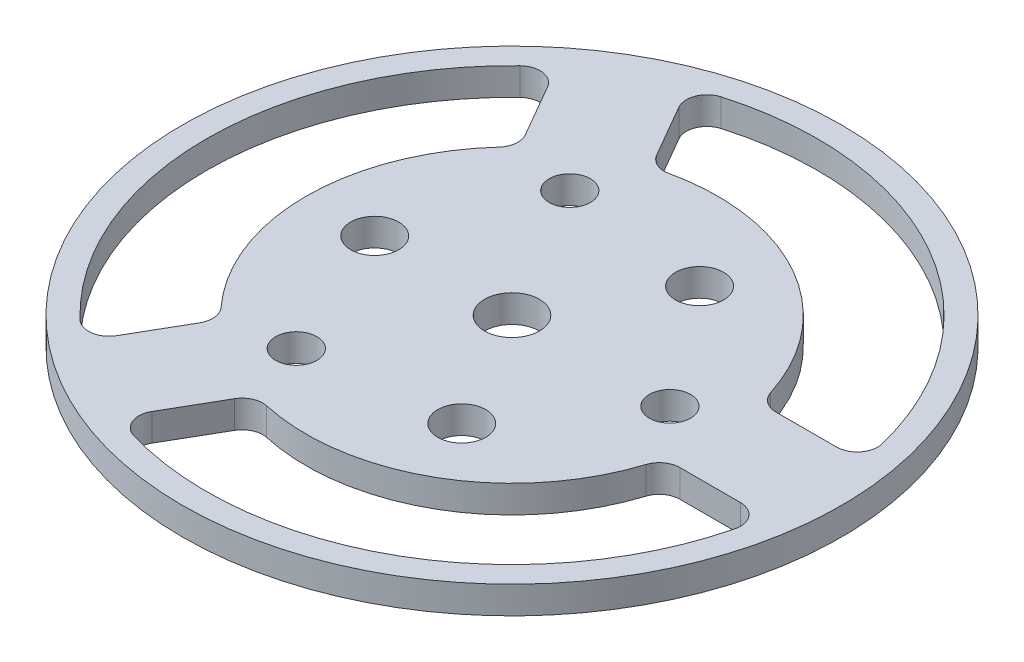
SolidWorks part; units mm, degrees
material "1060 Alloy"
ref_plane "Front Plane" through (0, 0, 0) normal (0, 0, 1) x (1, 0, 0)
ref_plane "Top Plane" through (0, 0, 0) normal (0, 1, 0) x (1, 0, 0)
ref_plane "Right Plane" through (0, 0, 0) normal (1, 0, 0) x (0, 0, -1)
sketch "Sketch1" plane through (0, 0, 0) normal (0, 1, 0) x (1, 0, 0)
  circle A0 centre (0, 0) radius 2
  circle A2 centre (0, 0) radius 24
  circle A3 centre (11.5, 0) radius 1.5
  circle A4 centre (-5.75, -9.9593) radius 1.5
  circle A5 centre (-5.75, 9.9593) radius 1.5
  point P13 (0, 0)
  dimension "D1" = 4
  dimension "D3" = 48
  dimension "D4" = 3
  dimension "D5" = 11.5
  dimension "D6" = 3
extrude "Boss-Extrude1" add sketch "Sketch1" along normal blind 2
sketch "Sketch2" plane through (0, 2, 0) normal (0, 1, 0) x (1, 0, 0)
  line L0 (21.973, 3.5) -> (14.586, 3.5)
  line L1 (21.973, -3.5) -> (14.586, -3.5)
  line L2 (-7.9554, -20.7792) -> (-4.2619, -14.3818)
  line L3 (-14.0176, -17.2792) -> (-10.3241, -10.8818)
  line L4 (-14.0176, 17.2792) -> (-10.3241, 10.8818)
  line L5 (-7.9554, 20.7792) -> (-4.2619, 14.3818)
  arc A0 (-14.0176, 17.2792) -> (-14.0176, -17.2792) centre (0, 0) ccw
  arc A1 (-10.3241, 10.8818) -> (-10.3241, -10.8818) centre (0, 0) ccw
  circle A2 centre (11.5, 0) radius 1.5 construction
  arc A3 (-4.2619, -14.3818) -> (14.586, -3.5) centre (0, 0) ccw
  arc A4 (-7.9554, -20.7792) -> (21.973, -3.5) centre (0, 0) ccw
  arc A5 (14.586, 3.5) -> (-4.2619, 14.3818) centre (0, 0) ccw
  arc A6 (21.973, 3.5) -> (-7.9554, 20.7792) centre (0, 0) ccw
  point P20 (0, 0)
  dimension "D1" = 44.5
  dimension "D2" = 30
  dimension "D3" = 3.5
  dimension "D4" = 3.5
  dimension "D5" = 3
extrude "Cut-Extrude1" cut sketch "Sketch2" against normal blind 2
fillet "Fillet1" radius 1.5 12 edges at (-4.2619, 1, 14.3818) (-7.9554, 1, -20.7792) (14.586, 1, 3.5) (21.973, 1, -3.5) (-14.0176, 1, 17.2792) (-4.2619, 1, -14.3818) (14.586, 1, -3.5) (-7.9554, 1, 20.7792) (21.973, 1, 3.5) (-10.3241, 1, 10.8818) (-10.3241, 1, -10.8818) (-14.0176, 1, -17.2792)
sketch "Sketch3" plane through (0, 2, 0) normal (0, 1, 0) x (1, 0, 0)
  line L0 (0, 0) -> (28.6123, 0) construction
  line L1 (0, 0) -> (7.5, 12.9904) construction
  circle A0 centre (5, 8.6603) radius 1.75
  arc A1 (14.2947, 4.5455) -> (-3.2109, 14.6523) centre (0, 0) ccw construction
  circle A2 centre (0, 0) radius 2 construction
  circle A3 centre (5, -8.6603) radius 1.75
  circle A4 centre (-10, 0) radius 1.75
  point P17 (0, 0)
  dimension "D1" = 3.5
  dimension "D2" = 10
  dimension "D3" = 3
extrude "Cut-Extrude2" cut sketch "Sketch3" against normal blind 10
